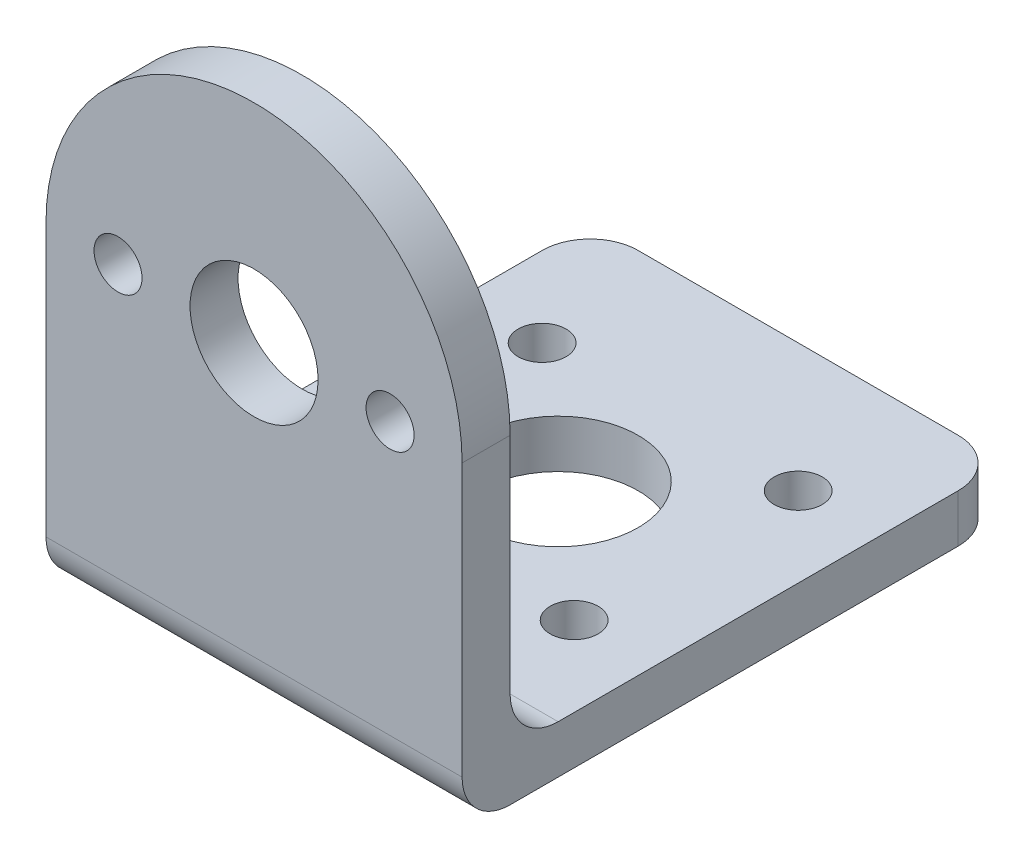
SolidWorks part; units mm, degrees
ref_plane "前视基准面" through (0, 0, 0) normal (0, 0, 1) x (1, 0, 0)
ref_plane "上视基准面" through (0, 0, 0) normal (0, 1, 0) x (1, 0, 0)
ref_plane "右视基准面" through (0, 0, 0) normal (1, 0, 0) x (0, 0, -1)
other "Configuration Table"
sketch "草图1" plane through (0, 0, 0) normal (0, 0, 1) x (1, 0, 0)
  line L0 (0, 4) -> (0, -4) construction
  line L1 (-13, 0) -> (-13, -20)
  line L2 (13, 0) -> (13, -20)
  line L3 (-13, -20) -> (13, -20)
  arc A4 (13, 0) -> (-13, 0) centre (0, 0) ccw
  circle A5 centre (0, 0) radius 4
  circle A6 centre (-8.5, 0) radius 1.5
  circle A7 centre (8.5, 0) radius 1.5
  point P11 (0, 0)
  dimension "D1" = 8
  dimension "D2" = 26
  dimension "D3" = 3
  dimension "D5" = 20
  dimension "D4" = 8.5
extrude "凸台-拉伸1" add sketch "草图1" along normal blind 3
sketch "草图2" plane through (0, 0, 0) normal (0, 0, 1) x (1, 0, 0)
  line L0 (-13, 0) -> (-13, -20) construction
  line L1 (-13, -17) -> (13, -17)
  line L2 (-13, -17) -> (-13, -20)
  line L3 (-13, -20) -> (13, -20)
  line L4 (13, -17) -> (13, -20)
  line L5 (-13, -20) -> (13, -20) construction
  dimension "D1" = 3
extrude "凸台-拉伸2" add sketch "草图2" against normal blind 31
sketch "草图3" plane through (0, 0, 0) normal (0, 1, 0) x (1, 0, 0)
  line L0 (-5, 16) -> (5, 16) construction
  line L1 (0, 21) -> (0, 11) construction
  line L2 (13, 31) -> (-13, 31) construction
  circle A0 centre (0, 16) radius 5
  circle A1 centre (-8, 23) radius 1.5
  circle A2 centre (8, 23) radius 1.5
  circle A3 centre (8, 9) radius 1.5
  circle A4 centre (-8, 9) radius 1.5
  dimension "D1" = 10
  dimension "D2" = 3
  dimension "D3" = 8
  dimension "D4" = 7
  dimension "D5" = 15
extrude "切除-拉伸1" cut sketch "草图3" against normal through all
fillet "圆角1" radius 3 4 edges at (-13, -18.5, -31) (13, -18.5, -31) (0, -17, 0) (0, -20, 3)
